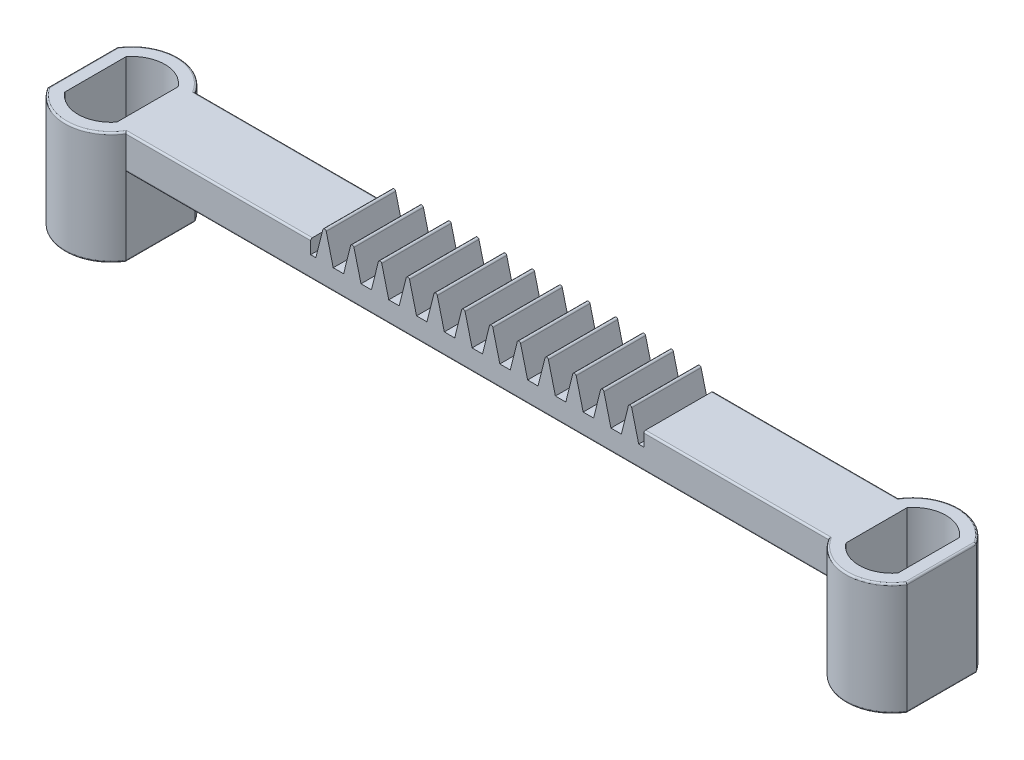
SolidWorks part; units mm, degrees
ref_plane "前视基准面" through (0, 0, 0) normal (0, 0, 1) x (1, 0, 0)
ref_plane "上视基准面" through (0, 0, 0) normal (0, 1, 0) x (1, 0, 0)
ref_plane "右视基准面" through (0, 0, 0) normal (1, 0, 0) x (0, 0, -1)
sketch "草图1" plane through (0, 0, 0) normal (0, 1, 0) x (1, 0, 0)
  line L0 (21, 2) -> (21, -2)
  line L1 (21, 2) -> (-21, 2)
  line L2 (21, -2) -> (-21, -2)
  line L3 (-21, 2) -> (-21, -2)
  line L4 (21, 2) -> (-21, -2) construction
  line L5 (21, -2) -> (-21, 2) construction
  point P1 (0, 0)
  dimension "D1" = 4
  dimension "D2" = 42
extrude "凸台-拉伸1" add sketch "草图1" along normal blind 2
sketch "草图2" plane through (0, 2, 0) normal (0, 1, 0) x (1, 0, 0)
  line L0 (21, 0) -> (22.5, 0) construction
  line L1 (21, -2) -> (21, 2) construction
  line L2 (20.25, 2) -> (20.25, -2)
  line L3 (22.5, 0) -> (22.5, -3.25) construction
  line L5 (24.75, 2) -> (24.75, -2)
  line L6 (20.25, 2) -> (24.75, -2) construction
  line L7 (20.25, -2) -> (24.75, 2) construction
  line L8 (22.5, 0) -> (22.5, 3.25) construction
  arc A0 (20.25, -2) -> (24.75, -2) centre (22.5, -0.6) ccw
  arc A1 (24.75, 2) -> (20.25, 2) centre (22.5, 0.6) ccw
  dimension "D1" = 1.5
  dimension "D2" = 4.5
  dimension "D3" = 4
  dimension "D4" = 3.25
  dimension "D5" = 3.25
extrude "凸台-拉伸2" add sketch "草图2" against normal blind 6.5
sketch "草图3" plane through (0, 2, 0) normal (0, 1, 0) x (1, 0, 0)
  line L5 (21, 1.7662) -> (21, -1.7662)
  line L6 (24, -1.7662) -> (24, 1.7662)
  arc A2 (21, -1.7662) -> (24, -1.7662) centre (22.5, -0.6) ccw
  arc A3 (24, 1.7662) -> (21, 1.7662) centre (22.5, 0.6) ccw
extrude "切除-拉伸1" cut sketch "草图3" against normal blind 5
sketch "草图4" plane through (0, -4.5, 0) normal (0, -1, 0) x (1, 0, 0)
  line L4 (23.75, -1.677) -> (23.75, 1.677)
  line L5 (21.25, 1.677) -> (21.25, -1.677)
  line L6 (23.75, -1.677) -> (23.75, 1.677)
  line L7 (21.25, 1.677) -> (21.25, -1.677)
  arc A4 (21.25, -1.677) -> (23.75, -1.677) centre (22.5, -0.6) ccw
  arc A5 (23.75, 1.677) -> (21.25, 1.677) centre (22.5, 0.6) ccw
  arc A6 (21.25, -1.677) -> (23.75, -1.677) centre (22.5, -0.6) ccw
  arc A7 (23.75, 1.677) -> (21.25, 1.677) centre (22.5, 0.6) ccw
  dimension "D1" = 1
extrude "切除-拉伸2" cut sketch "草图4" against normal blind 1.5
mirror "镜向1" about plane through (0, 0, 0) normal (1, 0, 0) of "切除-拉伸2", "切除-拉伸1", "凸台-拉伸2"
sketch "草图5" plane through (0, 0, 2) normal (0, 0, 1) x (1, 0, 0)
  line L0 (0, 0) -> (0, 2) construction
  line L1 (-20.25, 0) -> (20.25, 0) construction
  line L2 (-20.25, 2) -> (20.25, 2) construction
  line L3 (9.6, 2) -> (-9.6, 2)
  line L4 (-9.6, 2) -> (-9.6, 1.2)
  line L5 (-9.6, 1.2) -> (9.6, 1.2)
  line L6 (9.6, 2) -> (9.6, 1.2)
  point P10 (0, 1.2)
  dimension "D1" = 9.6
  dimension "D2" = 0.8
extrude "切除-拉伸3" cut sketch "草图5" against normal up to next
sketch "草图6" plane through (0, 0, 2) normal (0, 0, 1) x (1, 0, 0)
  line L0 (-9.6, 1.2) -> (-9.3, 1.2) construction
  line L1 (-9.6, 1.2) -> (9.6, 1.2) construction
  line L2 (-9.3, 1.2) -> (-8.3, 1.2)
  line L3 (-8.8, 1.2) -> (-8.8, 3.2) construction
  line L4 (-8.8, 3.2) -> (-9.3, 1.2)
  line L5 (-8.8, 3.2) -> (-8.3, 1.2)
  dimension "D1" = 0.3
  dimension "D2" = 1
  dimension "D3" = 2
extrude "凸台-拉伸3" add sketch "草图6" against normal blind 4
fillet "圆角1" radius 0.1 1 edges at (-8.8, 3.2, 0)
pattern_linear "阵列(线性)1" count 12 spacing 1.6 along (1, 0, 0) of "凸台-拉伸3", "圆角1"
fillet "圆角2" radius 0.1 20 edges at (14.925, 2, 2) (-14.925, 2, -2) (0, 0, -2) (14.925, 2, -2) (22.5, 2, 3.25) (24.75, 2, 0) (22.5, 2, -3.25) (20.25, -4.5, 0) (22.5, -4.5, -3.25) (24.75, -4.5, 0) (22.5, -4.5, 3.25) (0, 0, 2) (-14.925, 2, 2) (-22.5, 2, -3.25) (-22.5, 2, 3.25) (-24.75, 2, 0) (-22.5, -4.5, -3.25) (-20.25, -4.5, 0) (-22.5, -4.5, 3.25) (-24.75, -4.5, 0)
